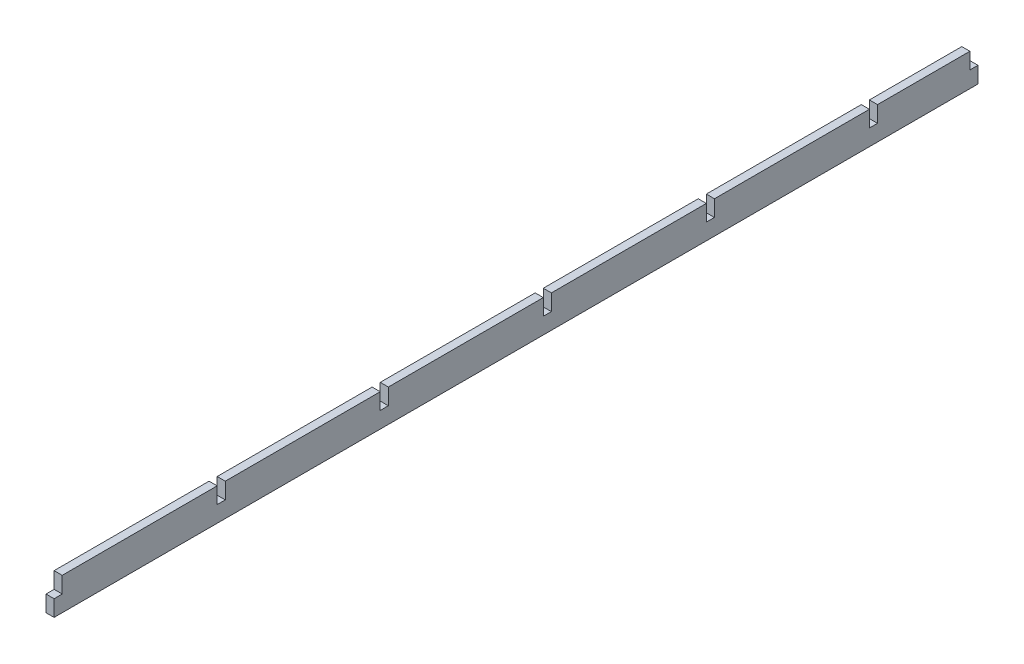
SolidWorks part; units mm, degrees
ref_plane "Front Plane" through (0, 0, 0) normal (0, 0, 1) x (1, 0, 0)
ref_plane "Top Plane" through (0, 0, 0) normal (0, 1, 0) x (1, 0, 0)
ref_plane "Right Plane" through (0, 0, 0) normal (1, 0, 0) x (0, 0, -1)
sketch "Sketch1" plane through (0, 0, 0) normal (1, 0, 0) x (0, 0, -1)
  line L1 (0, 0) -> (361.95, 0)
  line L2 (0, 0) -> (0, 12.7)
  line L3 (0, 12.7) -> (361.95, 12.7)
  line L4 (361.95, 0) -> (361.95, 12.7)
  dimension "D1" = 12.7
  dimension "D2" = 361.95
extrude "Boss-Extrude1" add sketch "Sketch1" along normal blind 3.175
sketch "Sketch2" plane through (3.175, 0, 0) normal (1, 0, 0) x (0, 0, -1)
  line L0 (361.95, 12.7) -> (0, 12.7) construction
  line L1 (0, 12.7) -> (3.175, 12.7)
  line L2 (0, 12.7) -> (0, 6.35)
  line L3 (0, 6.35) -> (3.175, 6.35)
  line L4 (3.175, 12.7) -> (3.175, 6.35)
  line L5 (63.881, 12.7) -> (67.056, 12.7)
  line L6 (63.881, 12.7) -> (63.881, 6.35)
  line L7 (63.881, 6.35) -> (67.056, 6.35)
  line L8 (67.056, 12.7) -> (67.056, 6.35)
  line L9 (127.762, 12.7) -> (130.937, 12.7)
  line L10 (127.762, 12.7) -> (127.762, 6.35)
  line L11 (127.762, 6.35) -> (130.937, 6.35)
  line L12 (130.937, 12.7) -> (130.937, 6.35)
  line L13 (191.643, 12.7) -> (194.818, 12.7)
  line L14 (191.643, 12.7) -> (191.643, 6.35)
  line L15 (191.643, 6.35) -> (194.818, 6.35)
  line L16 (194.818, 12.7) -> (194.818, 6.35)
  line L21 (255.524, 12.7) -> (258.699, 12.7)
  line L22 (255.524, 12.7) -> (255.524, 6.35)
  line L23 (255.524, 6.35) -> (258.699, 6.35)
  line L24 (258.699, 12.7) -> (258.699, 6.35)
  line L25 (319.405, 12.7) -> (322.58, 12.7)
  line L26 (319.405, 12.7) -> (319.405, 6.35)
  line L27 (319.405, 6.35) -> (322.58, 6.35)
  line L28 (322.58, 12.7) -> (322.58, 6.35)
  line L29 (358.775, 12.7) -> (361.95, 12.7)
  line L30 (358.775, 12.7) -> (358.775, 6.35)
  line L31 (358.775, 6.35) -> (361.95, 6.35)
  line L32 (361.95, 12.7) -> (361.95, 6.35)
  point P26 (349.1606, 11.0659)
  point P27 (357.0498, 11.6294)
  point P28 (361.95, 12.7)
  dimension "D1" = 3.175
  dimension "D2" = 6.35
  dimension "D3" = 60.706
  dimension "D4" = 3.175
  dimension "D5" = 6.35
  dimension "D6" = 3.175
  dimension "D7" = 6.35
  dimension "D8" = 3.175
  dimension "D9" = 6.35
  dimension "D10" = 3.175
  dimension "D11" = 6.35
  dimension "D12" = 60.706
  dimension "D13" = 60.706
  dimension "D14" = 60.706
  dimension "D15" = 3.175
  dimension "D16" = 6.35
  dimension "D17" = 60.706
  dimension "D18" = 3.175
  dimension "D19" = 6.35
extrude "Cut-Extrude1" cut sketch "Sketch2" against normal blind 5.715
